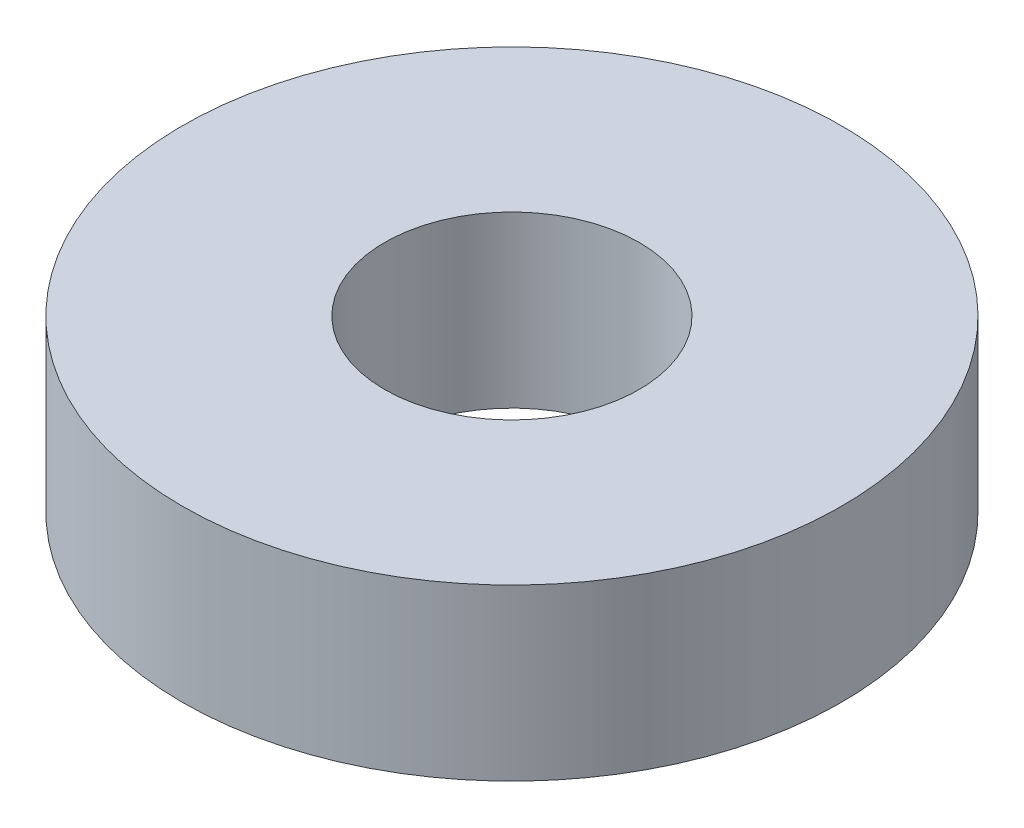
SolidWorks part; units mm, degrees
ref_plane "Front Plane" through (0, 0, 0) normal (0, 0, 1) x (1, 0, 0)
ref_plane "Top Plane" through (0, 0, 0) normal (0, 1, 0) x (1, 0, 0)
ref_plane "Right Plane" through (0, 0, 0) normal (1, 0, 0) x (0, 0, -1)
sketch "Sketch1" plane through (0, 0, 0) normal (0, 1, 0) x (1, 0, 0)
  circle A0 centre (0, 0) radius 3.15
  circle A1 centre (0, 0) radius 8.15
  dimension "D1" = 6.3
  dimension "D2" = 16.3
extrude "Boss-Extrude1" add sketch "Sketch1" along normal blind 4.2
equation "\"D2@Sketch1\"=\"D1@Sketch1\"+10"
